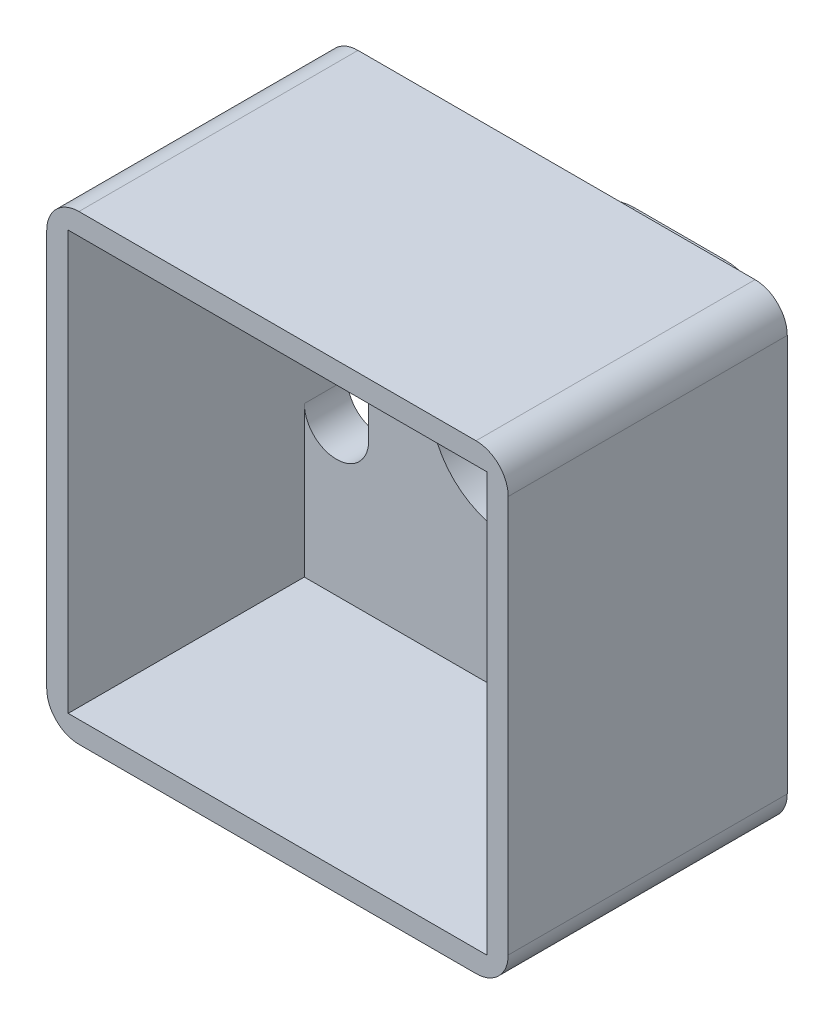
SolidWorks part; units mm, degrees
ref_plane "Front Plane" through (0, 0, 0) normal (1, 0, 0) x (0, 1, 0)
ref_plane "Top Plane" through (0, 0, 0) normal (0, 0, 1) x (0, 1, 0)
ref_plane "Right Plane" through (0, 0, 0) normal (0, 1, 0) x (-1, 0, 0)
sketch "Sketch1" plane through (0, 0, 0) normal (0, 0, 1) x (0, 1, 0)
  line L1 (0, 0) -> (-39, 0)
  line L2 (0, 0) -> (0, 39)
  line L3 (0, 39) -> (-39, 39)
  line L4 (-39, 0) -> (-39, 39)
  line L5 (-41, 41) -> (2, 41)
  line L6 (-41, 41) -> (-41, -2)
  line L7 (-41, -2) -> (2, -2)
  line L8 (2, 41) -> (2, -2)
  dimension "D1" = 39
  dimension "D2" = 39
  dimension "D3" = 2
  dimension "D4" = 2
  dimension "D5" = 2
  dimension "D6" = 2
  dimension "D7" = 43
extrude "Boss-Extrude1" add sketch "Sketch1" along normal blind 38 contours L6 L7 L8 L5
sketch "Sketch3" plane through (0, 0, 38) normal (0, 0, 1) x (1, 0, 0)
  line L0 (-3, -13) -> (-3, -25) construction
  line L1 (-39, 0) -> (0, 0)
  line L2 (-39, 0) -> (-39, -39.3012)
  line L3 (-39, -39.3012) -> (0, -39.3012)
  line L4 (0, 0) -> (0, -39.3012)
  line L5 (0, -13) -> (0, -25)
  line L6 (-6, -13) -> (-6, -25)
  line L7 (-36, -13) -> (-36, -25) construction
  line L8 (-33, -13) -> (-33, -25)
  line L9 (-39, -13) -> (-39, -25)
  circle A0 centre (-20, -19) radius 7.25
  arc A1 (0, -13) -> (-6, -13) centre (-3, -13) ccw
  arc A2 (-6, -25) -> (0, -25) centre (-3, -25) ccw
  arc A3 (-33, -13) -> (-39, -13) centre (-36, -13) ccw
  arc A4 (-39, -25) -> (-33, -25) centre (-36, -25) ccw
  circle A5 centre (-20, -3.5068) radius 3
  point P12 (-3, -19)
  point P20 (-36, -19)
  dimension "D7" = 14.5
  dimension "D8" = 12
  dimension "D14" = 6
  dimension "D16" = 3
  dimension "D17" = 3
  dimension "D9" = 12
  dimension "D1" = 2
  dimension "D2" = 1.6988
  dimension "D3" = 2
  dimension "D4" = 2
  dimension "D5" = 19
  dimension "D6" = 19
  dimension "D10" = 3
  dimension "D11" = 3
  dimension "D12" = 19
  dimension "D13" = 19
  dimension "D15" = 19
extrude "Cut-Extrude4" cut sketch "Sketch3" against normal blind 38 contours A5 | A0 | L6 A2 L5 A1 | L8 A4 L9 A3
sketch "Sketch6" plane through (0, 0, 38) normal (0, 0, 1) x (1, 0, 0)
  line L1 (-41, 2) -> (2, 2)
  line L2 (-41, 2) -> (-41, -41)
  line L3 (-41, -41) -> (2, -41)
  line L4 (2, 2) -> (2, -41)
  line L12 (-39, 0) -> (-39, -39)
  line L13 (-39, -39) -> (0, -39)
  line L14 (0, -39) -> (0, 0)
  line L15 (0, 0) -> (-39, 0)
  line L16 (-39, 0) -> (-39, -39)
  line L17 (-39, -39) -> (0, -39)
  line L18 (0, -39) -> (0, 0)
  line L19 (0, 0) -> (-39, 0)
  point P6 (0, 0)
  point P7 (0, 0)
  dimension "D1" = 2
extrude "Cut-Extrude5" cut sketch "Sketch6" against normal blind 22 contours L19 L16 L17 L18
sketch "Sketch7" plane through (0, 0, 0) normal (0, 0, -1) x (1, 0, 0)
  line L1 (-29.2126, 9.8159) -> (-10.8126, 9.8159)
  line L2 (-29.2126, 9.8159) -> (-29.2126, 28.2159)
  line L3 (-29.2126, 28.2159) -> (-10.8126, 28.2159)
  line L4 (-10.8126, 9.8159) -> (-10.8126, 28.2159)
  line L5 (-29.2126, 9.8159) -> (-10.8126, 28.2159) construction
  line L6 (-29.2126, 28.2159) -> (-10.8126, 9.8159) construction
  line L7 (-41, 41) -> (2, 41)
  line L8 (-41, 41) -> (-41, -2)
  line L9 (-41, -2) -> (2, -2)
  line L10 (2, 41) -> (2, -2)
  circle A0 centre (-20.0126, 19.0159) radius 7.0001
  point P12 (-41, 41)
  circle M6 centre (-20, 3.5068) radius 3
  line M8 (-6, 13) -> (-6, 25)
  arc M9 (-6, 25) -> (0, 25) centre (-3, 25) cw
  line M10 (0, 25) -> (0, 13)
  arc M11 (0, 13) -> (-6, 13) centre (-3, 13) cw
  arc M12 (-33, 13) -> (-39, 13) centre (-36, 13) cw
  line M13 (-39, 13) -> (-39, 25)
  arc M14 (-39, 25) -> (-33, 25) centre (-36, 25) cw
  line M15 (-33, 25) -> (-33, 13)
  line M16 (-41, 41) -> (-41, -2)
  line M17 (-41, -2) -> (2, -2)
  line M18 (2, -2) -> (2, 41)
  line M19 (2, 41) -> (-41, 41)
  dimension "D1" = 18.4
  dimension "D2" = 18.4
extrude "Cut-Extrude8" cut sketch "Sketch7" against normal blind 12 contours L4 L1 L2 L3 M19 M16 M17 M18 M15 M12 M13 M14 M11 M8 M9 M10 M6
fillet "Fillet2" radius 5 4 edges at (-29.2126, -28.2159, 6) (-29.2126, -9.8159, 6) (-10.8126, -9.8159, 6) (-10.8126, -28.2159, 6)
fillet "Fillet3" radius 3 4 edges at (2, 2, 25) (-41, 2, 25) (-41, -41, 25) (2, -41, 25)
